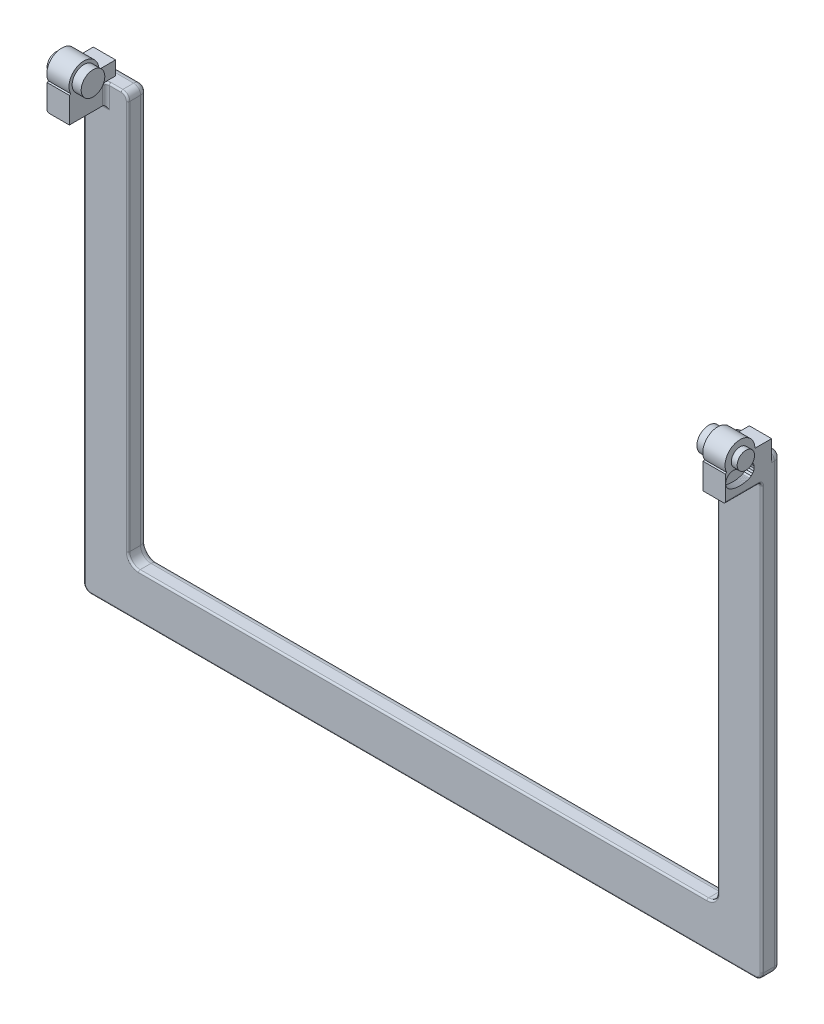
SolidWorks part; units mm, degrees
ref_plane "Спереди" through (0, 0, 0) normal (0, 0, 1) x (1, 0, 0)
ref_plane "Сверху" through (0, 0, 0) normal (0, 1, 0) x (1, 0, 0)
ref_plane "Справа" through (0, 0, 0) normal (1, 0, 0) x (0, 0, -1)
other "Configuration Table"
sketch "Foot_crossbar_profile" plane through (0, 0, 0) normal (0, 0, 1) x (1, 0, 0)
  line L0 (-0.6, -9) -> (190.6, -9)
  line L1 (192.6, -7) -> (192.6, 1.8)
  line L2 (190.6, 3.8) -> (-0.6, 3.8)
  line L3 (-2.6, 1.8) -> (-2.6, -7)
  arc A0 (190.6, -9) -> (192.6, -7) centre (190.6, -7) ccw
  arc A1 (192.6, 1.8) -> (190.6, 3.8) centre (190.6, 1.8) ccw
  arc A2 (-0.6, 3.8) -> (-2.6, 1.8) centre (-0.6, 1.8) ccw
  arc A3 (-2.6, -7) -> (-0.6, -9) centre (-0.6, -7) ccw
sketch "Right_leg_profile" plane through (0, 0, 0) normal (0, 0, 1) x (1, 0, 0)
  line L0 (181.8, -6.6) -> (190.6, -6.6)
  line L1 (192.6, -4.6) -> (192.6, 123)
  line L2 (190.6, 125) -> (181.8, 125)
  line L3 (179.8, 123) -> (179.8, -4.6)
  arc A0 (190.6, -6.6) -> (192.6, -4.6) centre (190.6, -4.6) ccw
  arc A1 (192.6, 123) -> (190.6, 125) centre (190.6, 123) ccw
  arc A2 (181.8, 125) -> (179.8, 123) centre (181.8, 123) ccw
  arc A3 (179.8, -4.6) -> (181.8, -6.6) centre (181.8, -4.6) ccw
sketch "Pivot_neck_0_profile" plane through (0, 0, 0) normal (1, 0, 0) x (0, 0, -1)
  line L0 (15.3, 115.4) -> (15.3, 125)
  line L1 (15.3, 125) -> (6.2, 125)
  line L2 (6.2, 125) -> (2, 122.8)
  line L3 (2, 122.8) -> (2, 115.4)
  line L4 (2, 115.4) -> (15.3, 115.4)
sketch "Pivot_lug_0_profile" plane through (0, 0, 0) normal (1, 0, 0) x (0, 0, -1)
  circle A0 centre (6.2, 125) radius 4.3
sketch "Captive_axle_0_profile" plane through (0, 0, 0) normal (1, 0, 0) x (0, 0, -1)
  circle A0 centre (6.2, 125) radius 2.5
sketch "Blind_rotation_groove_0_profile" plane through (0, 0, 0) normal (1, 0, 0) x (0, 0, -1)
  line L0 (8.9553, 118.3481) -> (8.7362, 118.2615)
  line L1 (8.7362, 118.2615) -> (8.5144, 118.1821)
  line L2 (8.5144, 118.1821) -> (8.29, 118.11)
  line L3 (8.29, 118.11) -> (8.0635, 118.0453)
  line L4 (8.0635, 118.0453) -> (7.8349, 117.9881)
  line L5 (7.8349, 117.9881) -> (7.6047, 117.9383)
  line L6 (7.6047, 117.9383) -> (7.3728, 117.8962)
  line L7 (7.3728, 117.8962) -> (7.1398, 117.8616)
  line L8 (7.1398, 117.8616) -> (6.9057, 117.8347)
  line L9 (6.9057, 117.8347) -> (6.6709, 117.8154)
  line L10 (6.6709, 117.8154) -> (6.4356, 117.8039)
  line L11 (6.4356, 117.8039) -> (6.2, 117.8)
  line L12 (6.2, 117.8) -> (5.9644, 117.8039)
  line L13 (5.9644, 117.8039) -> (5.7291, 117.8154)
  line L14 (5.7291, 117.8154) -> (5.4943, 117.8347)
  line L15 (5.4943, 117.8347) -> (5.2602, 117.8616)
  line L16 (5.2602, 117.8616) -> (5.0272, 117.8962)
  line L17 (5.0272, 117.8962) -> (4.7953, 117.9383)
  line L18 (4.7953, 117.9383) -> (4.5651, 117.9881)
  line L19 (4.5651, 117.9881) -> (4.3365, 118.0453)
  line L20 (4.3365, 118.0453) -> (4.11, 118.11)
  line L21 (4.11, 118.11) -> (3.8856, 118.1821)
  line L22 (3.8856, 118.1821) -> (3.6638, 118.2615)
  line L23 (3.6638, 118.2615) -> (3.4447, 118.3481)
  line L24 (3.4447, 118.3481) -> (2.9473, 118.6352)
  line L25 (2.9473, 118.6352) -> (2.5412, 119.0413)
  line L26 (2.5412, 119.0413) -> (2.254, 119.5387)
  line L27 (2.254, 119.5387) -> (2.1054, 120.0934)
  line L28 (2.1054, 120.0934) -> (2.1054, 120.6678)
  line L29 (2.1054, 120.6678) -> (2.254, 121.2225)
  line L30 (2.254, 121.2225) -> (2.5412, 121.7199)
  line L31 (2.5412, 121.7199) -> (2.9473, 122.126)
  line L32 (2.9473, 122.126) -> (3.4447, 122.4131)
  line L33 (3.4447, 122.4131) -> (3.9994, 122.5618)
  line L34 (3.9994, 122.5618) -> (4.5737, 122.5618)
  line L35 (4.5737, 122.5618) -> (5.1285, 122.4131)
  line L36 (5.1285, 122.4131) -> (5.2137, 122.3795)
  line L37 (5.2137, 122.3795) -> (5.3, 122.3486)
  line L38 (5.3, 122.3486) -> (5.3872, 122.3206)
  line L39 (5.3872, 122.3206) -> (5.4753, 122.2954)
  line L40 (5.4753, 122.2954) -> (5.5642, 122.2731)
  line L41 (5.5642, 122.2731) -> (5.6537, 122.2538)
  line L42 (5.6537, 122.2538) -> (5.7439, 122.2374)
  line L43 (5.7439, 122.2374) -> (5.8345, 122.224)
  line L44 (5.8345, 122.224) -> (5.9256, 122.2135)
  line L45 (5.9256, 122.2135) -> (6.0169, 122.206)
  line L46 (6.0169, 122.206) -> (6.1084, 122.2015)
  line L47 (6.1084, 122.2015) -> (6.2, 122.2)
  line L48 (6.2, 122.2) -> (6.2916, 122.2015)
  line L49 (6.2916, 122.2015) -> (6.3831, 122.206)
  line L50 (6.3831, 122.206) -> (6.4744, 122.2135)
  line L51 (6.4744, 122.2135) -> (6.5655, 122.224)
  line L52 (6.5655, 122.224) -> (6.6561, 122.2374)
  line L53 (6.6561, 122.2374) -> (6.7463, 122.2538)
  line L54 (6.7463, 122.2538) -> (6.8358, 122.2731)
  line L55 (6.8358, 122.2731) -> (6.9247, 122.2954)
  line L56 (6.9247, 122.2954) -> (7.0128, 122.3206)
  line L57 (7.0128, 122.3206) -> (7.1, 122.3486)
  line L58 (7.1, 122.3486) -> (7.1863, 122.3795)
  line L59 (7.1863, 122.3795) -> (7.2715, 122.4131)
  line L60 (7.2715, 122.4131) -> (7.8263, 122.5618)
  line L61 (7.8263, 122.5618) -> (8.4006, 122.5618)
  line L62 (8.4006, 122.5618) -> (8.9553, 122.4131)
  line L63 (8.9553, 122.4131) -> (9.4527, 122.126)
  line L64 (9.4527, 122.126) -> (9.8588, 121.7199)
  line L65 (9.8588, 121.7199) -> (10.146, 121.2225)
  line L66 (10.146, 121.2225) -> (10.2946, 120.6678)
  line L67 (10.2946, 120.6678) -> (10.2946, 120.0934)
  line L68 (10.2946, 120.0934) -> (10.146, 119.5387)
  line L69 (10.146, 119.5387) -> (9.8588, 119.0413)
  line L70 (9.8588, 119.0413) -> (9.4527, 118.6352)
  line L71 (9.4527, 118.6352) -> (8.9553, 118.3481)
sketch "Pivot_neck_1_profile" plane through (0, 0, 0) normal (1, 0, 0) x (0, 0, -1)
  line L0 (15.3, 115.4) -> (15.3, 125)
  line L1 (15.3, 125) -> (6.2, 125)
  line L2 (6.2, 125) -> (2, 122.8)
  line L3 (2, 122.8) -> (2, 115.4)
  line L4 (2, 115.4) -> (15.3, 115.4)
sketch "Pivot_lug_1_profile" plane through (0, 0, 0) normal (1, 0, 0) x (0, 0, -1)
  circle A0 centre (6.2, 125) radius 4.3
sketch "Captive_axle_1_profile" plane through (0, 0, 0) normal (1, 0, 0) x (0, 0, -1)
  circle A0 centre (6.2, 125) radius 2.5
sketch "Blind_rotation_groove_1_profile" plane through (0, 0, 0) normal (1, 0, 0) x (0, 0, -1)
  line L0 (8.9553, 118.3481) -> (8.7362, 118.2615)
  line L1 (8.7362, 118.2615) -> (8.5144, 118.1821)
  line L2 (8.5144, 118.1821) -> (8.29, 118.11)
  line L3 (8.29, 118.11) -> (8.0635, 118.0453)
  line L4 (8.0635, 118.0453) -> (7.8349, 117.9881)
  line L5 (7.8349, 117.9881) -> (7.6047, 117.9383)
  line L6 (7.6047, 117.9383) -> (7.3728, 117.8962)
  line L7 (7.3728, 117.8962) -> (7.1398, 117.8616)
  line L8 (7.1398, 117.8616) -> (6.9057, 117.8347)
  line L9 (6.9057, 117.8347) -> (6.6709, 117.8154)
  line L10 (6.6709, 117.8154) -> (6.4356, 117.8039)
  line L11 (6.4356, 117.8039) -> (6.2, 117.8)
  line L12 (6.2, 117.8) -> (5.9644, 117.8039)
  line L13 (5.9644, 117.8039) -> (5.7291, 117.8154)
  line L14 (5.7291, 117.8154) -> (5.4943, 117.8347)
  line L15 (5.4943, 117.8347) -> (5.2602, 117.8616)
  line L16 (5.2602, 117.8616) -> (5.0272, 117.8962)
  line L17 (5.0272, 117.8962) -> (4.7953, 117.9383)
  line L18 (4.7953, 117.9383) -> (4.5651, 117.9881)
  line L19 (4.5651, 117.9881) -> (4.3365, 118.0453)
  line L20 (4.3365, 118.0453) -> (4.11, 118.11)
  line L21 (4.11, 118.11) -> (3.8856, 118.1821)
  line L22 (3.8856, 118.1821) -> (3.6638, 118.2615)
  line L23 (3.6638, 118.2615) -> (3.4447, 118.3481)
  line L24 (3.4447, 118.3481) -> (2.9473, 118.6352)
  line L25 (2.9473, 118.6352) -> (2.5412, 119.0413)
  line L26 (2.5412, 119.0413) -> (2.254, 119.5387)
  line L27 (2.254, 119.5387) -> (2.1054, 120.0934)
  line L28 (2.1054, 120.0934) -> (2.1054, 120.6678)
  line L29 (2.1054, 120.6678) -> (2.254, 121.2225)
  line L30 (2.254, 121.2225) -> (2.5412, 121.7199)
  line L31 (2.5412, 121.7199) -> (2.9473, 122.126)
  line L32 (2.9473, 122.126) -> (3.4447, 122.4131)
  line L33 (3.4447, 122.4131) -> (3.9994, 122.5618)
  line L34 (3.9994, 122.5618) -> (4.5737, 122.5618)
  line L35 (4.5737, 122.5618) -> (5.1285, 122.4131)
  line L36 (5.1285, 122.4131) -> (5.2137, 122.3795)
  line L37 (5.2137, 122.3795) -> (5.3, 122.3486)
  line L38 (5.3, 122.3486) -> (5.3872, 122.3206)
  line L39 (5.3872, 122.3206) -> (5.4753, 122.2954)
  line L40 (5.4753, 122.2954) -> (5.5642, 122.2731)
  line L41 (5.5642, 122.2731) -> (5.6537, 122.2538)
  line L42 (5.6537, 122.2538) -> (5.7439, 122.2374)
  line L43 (5.7439, 122.2374) -> (5.8345, 122.224)
  line L44 (5.8345, 122.224) -> (5.9256, 122.2135)
  line L45 (5.9256, 122.2135) -> (6.0169, 122.206)
  line L46 (6.0169, 122.206) -> (6.1084, 122.2015)
  line L47 (6.1084, 122.2015) -> (6.2, 122.2)
  line L48 (6.2, 122.2) -> (6.2916, 122.2015)
  line L49 (6.2916, 122.2015) -> (6.3831, 122.206)
  line L50 (6.3831, 122.206) -> (6.4744, 122.2135)
  line L51 (6.4744, 122.2135) -> (6.5655, 122.224)
  line L52 (6.5655, 122.224) -> (6.6561, 122.2374)
  line L53 (6.6561, 122.2374) -> (6.7463, 122.2538)
  line L54 (6.7463, 122.2538) -> (6.8358, 122.2731)
  line L55 (6.8358, 122.2731) -> (6.9247, 122.2954)
  line L56 (6.9247, 122.2954) -> (7.0128, 122.3206)
  line L57 (7.0128, 122.3206) -> (7.1, 122.3486)
  line L58 (7.1, 122.3486) -> (7.1863, 122.3795)
  line L59 (7.1863, 122.3795) -> (7.2715, 122.4131)
  line L60 (7.2715, 122.4131) -> (7.8263, 122.5618)
  line L61 (7.8263, 122.5618) -> (8.4006, 122.5618)
  line L62 (8.4006, 122.5618) -> (8.9553, 122.4131)
  line L63 (8.9553, 122.4131) -> (9.4527, 122.126)
  line L64 (9.4527, 122.126) -> (9.8588, 121.7199)
  line L65 (9.8588, 121.7199) -> (10.146, 121.2225)
  line L66 (10.146, 121.2225) -> (10.2946, 120.6678)
  line L67 (10.2946, 120.6678) -> (10.2946, 120.0934)
  line L68 (10.2946, 120.0934) -> (10.146, 119.5387)
  line L69 (10.146, 119.5387) -> (9.8588, 119.0413)
  line L70 (9.8588, 119.0413) -> (9.4527, 118.6352)
  line L71 (9.4527, 118.6352) -> (8.9553, 118.3481)
sketch "Left_leg_profile" plane through (0, 0, 0) normal (0, 0, 1) x (1, 0, 0)
  line L0 (-0.6, -6.6) -> (8.2, -6.6)
  line L1 (10.2, -4.6) -> (10.2, 119)
  line L2 (8.2, 121) -> (-0.6, 121)
  line L3 (-2.6, 119) -> (-2.6, -4.6)
  arc A0 (8.2, -6.6) -> (10.2, -4.6) centre (8.2, -4.6) ccw
  arc A1 (10.2, 119) -> (8.2, 121) centre (8.2, 119) ccw
  arc A2 (-0.6, 121) -> (-2.6, 119) centre (-0.6, 119) ccw
  arc A3 (-2.6, -4.6) -> (-0.6, -6.6) centre (-0.6, -4.6) ccw
extrude "Left_leg" add sketch "Left_leg_profile" along normal blind 5.6 from offset 18.1
sketch "Эскиз2" plane through (0, 0, 0) normal (0, 0, 1) x (1, 0, 0)
  line L0 (-0.6, -9) -> (190.6, -9)
  line L1 (192.6, -7) -> (192.6, 1.8)
  line L2 (190.6, 3.8) -> (-0.6, 3.8)
  line L3 (-2.6, 1.8) -> (-2.6, -7)
  arc A0 (190.6, -9) -> (192.6, -7) centre (190.6, -7) ccw
  arc A1 (192.6, 1.8) -> (190.6, 3.8) centre (190.6, 1.8) ccw
  arc A2 (-0.6, 3.8) -> (-2.6, 1.8) centre (-0.6, 1.8) ccw
  arc A3 (-2.6, -7) -> (-0.6, -9) centre (-0.6, -7) ccw
extrude "Foot_crossbar" add sketch "Эскиз2" along normal blind 5.6 from offset 18.1
sketch "Эскиз3" plane through (0, 0, 0) normal (0, 0, 1) x (1, 0, 0)
  line L0 (181.8, -6.6) -> (190.6, -6.6)
  line L1 (192.6, -4.6) -> (192.6, 119)
  line L2 (190.6, 121) -> (181.8, 121)
  line L3 (179.8, 119) -> (179.8, -4.6)
  arc A0 (190.6, -6.6) -> (192.6, -4.6) centre (190.6, -4.6) ccw
  arc A1 (192.6, 119) -> (190.6, 121) centre (190.6, 119) ccw
  arc A2 (181.8, 121) -> (179.8, 119) centre (181.8, 119) ccw
  arc A3 (179.8, -4.6) -> (181.8, -6.6) centre (181.8, -4.6) ccw
extrude "Right_leg" add sketch "Эскиз3" along normal blind 5.6 from offset 18.1
sketch "Эскиз4" plane through (0, 0, 0) normal (1, 0, 0) x (0, 0, -1)
  line L0 (15.3, 115.4) -> (15.3, 125)
  line L1 (15.3, 125) -> (6.2, 125)
  line L2 (6.2, 125) -> (2, 122.8)
  line L3 (2, 122.8) -> (2, 115.4)
  line L4 (2, 115.4) -> (15.3, 115.4)
extrude "Pivot_neck_0" add sketch "Эскиз4" along normal blind 6.4 from offset 2.6
sketch "Эскиз5" plane through (0, 0, 0) normal (1, 0, 0) x (0, 0, -1)
  circle A0 centre (6.2, 125) radius 4.3
extrude "Pivot_lug_0" add sketch "Эскиз5" along normal blind 6.4 from offset 2.6
sketch "Glass_keeper_0_profile" plane through (0, 0, 0) normal (1, 0, 0) x (0, 0, -1)
  circle A0 centre (6.2, 125) radius 3.4
extrude "Glass_keeper_0" add sketch "Glass_keeper_0_profile" along normal blind 2.8 from offset 3.6
sketch "Эскиз7" plane through (0, 0, 0) normal (1, 0, 0) x (0, 0, -1)
  circle A0 centre (6.2, 125) radius 2.5
extrude "Captive_axle_0" add sketch "Эскиз7" along normal blind 2 from offset 4.3
sketch "Эскиз8" plane through (0, 0, 0) normal (1, 0, 0) x (0, 0, -1)
  line L0 (8.9553, 118.3481) -> (8.7362, 118.2615)
  line L1 (8.7362, 118.2615) -> (8.5144, 118.1821)
  line L2 (8.5144, 118.1821) -> (8.29, 118.11)
  line L3 (8.29, 118.11) -> (8.0635, 118.0453)
  line L4 (8.0635, 118.0453) -> (7.8349, 117.9881)
  line L5 (7.8349, 117.9881) -> (7.6047, 117.9383)
  line L6 (7.6047, 117.9383) -> (7.3728, 117.8962)
  line L7 (7.3728, 117.8962) -> (7.1398, 117.8616)
  line L8 (7.1398, 117.8616) -> (6.9057, 117.8347)
  line L9 (6.9057, 117.8347) -> (6.6709, 117.8154)
  line L10 (6.6709, 117.8154) -> (6.4356, 117.8039)
  line L11 (6.4356, 117.8039) -> (6.2, 117.8)
  line L12 (6.2, 117.8) -> (5.9644, 117.8039)
  line L13 (5.9644, 117.8039) -> (5.7291, 117.8154)
  line L14 (5.7291, 117.8154) -> (5.4943, 117.8347)
  line L15 (5.4943, 117.8347) -> (5.2602, 117.8616)
  line L16 (5.2602, 117.8616) -> (5.0272, 117.8962)
  line L17 (5.0272, 117.8962) -> (4.7953, 117.9383)
  line L18 (4.7953, 117.9383) -> (4.5651, 117.9881)
  line L19 (4.5651, 117.9881) -> (4.3365, 118.0453)
  line L20 (4.3365, 118.0453) -> (4.11, 118.11)
  line L21 (4.11, 118.11) -> (3.8856, 118.1821)
  line L22 (3.8856, 118.1821) -> (3.6638, 118.2615)
  line L23 (3.6638, 118.2615) -> (3.4447, 118.3481)
  line L24 (3.4447, 118.3481) -> (2.9473, 118.6352)
  line L25 (2.9473, 118.6352) -> (2.5412, 119.0413)
  line L26 (2.5412, 119.0413) -> (2.254, 119.5387)
  line L27 (2.254, 119.5387) -> (2.1054, 120.0934)
  line L28 (2.1054, 120.0934) -> (2.1054, 120.6678)
  line L29 (2.1054, 120.6678) -> (2.254, 121.2225)
  line L30 (2.254, 121.2225) -> (2.5412, 121.7199)
  line L31 (2.5412, 121.7199) -> (2.9473, 122.126)
  line L32 (2.9473, 122.126) -> (3.4447, 122.4131)
  line L33 (3.4447, 122.4131) -> (3.9994, 122.5618)
  line L34 (3.9994, 122.5618) -> (4.5737, 122.5618)
  line L35 (4.5737, 122.5618) -> (5.1285, 122.4131)
  line L36 (5.1285, 122.4131) -> (5.2137, 122.3795)
  line L37 (5.2137, 122.3795) -> (5.3, 122.3486)
  line L38 (5.3, 122.3486) -> (5.3872, 122.3206)
  line L39 (5.3872, 122.3206) -> (5.4753, 122.2954)
  line L40 (5.4753, 122.2954) -> (5.5642, 122.2731)
  line L41 (5.5642, 122.2731) -> (5.6537, 122.2538)
  line L42 (5.6537, 122.2538) -> (5.7439, 122.2374)
  line L43 (5.7439, 122.2374) -> (5.8345, 122.224)
  line L44 (5.8345, 122.224) -> (5.9256, 122.2135)
  line L45 (5.9256, 122.2135) -> (6.0169, 122.206)
  line L46 (6.0169, 122.206) -> (6.1084, 122.2015)
  line L47 (6.1084, 122.2015) -> (6.2, 122.2)
  line L48 (6.2, 122.2) -> (6.2916, 122.2015)
  line L49 (6.2916, 122.2015) -> (6.3831, 122.206)
  line L50 (6.3831, 122.206) -> (6.4744, 122.2135)
  line L51 (6.4744, 122.2135) -> (6.5655, 122.224)
  line L52 (6.5655, 122.224) -> (6.6561, 122.2374)
  line L53 (6.6561, 122.2374) -> (6.7463, 122.2538)
  line L54 (6.7463, 122.2538) -> (6.8358, 122.2731)
  line L55 (6.8358, 122.2731) -> (6.9247, 122.2954)
  line L56 (6.9247, 122.2954) -> (7.0128, 122.3206)
  line L57 (7.0128, 122.3206) -> (7.1, 122.3486)
  line L58 (7.1, 122.3486) -> (7.1863, 122.3795)
  line L59 (7.1863, 122.3795) -> (7.2715, 122.4131)
  line L60 (7.2715, 122.4131) -> (7.8263, 122.5618)
  line L61 (7.8263, 122.5618) -> (8.4006, 122.5618)
  line L62 (8.4006, 122.5618) -> (8.9553, 122.4131)
  line L63 (8.9553, 122.4131) -> (9.4527, 122.126)
  line L64 (9.4527, 122.126) -> (9.8588, 121.7199)
  line L65 (9.8588, 121.7199) -> (10.146, 121.2225)
  line L66 (10.146, 121.2225) -> (10.2946, 120.6678)
  line L67 (10.2946, 120.6678) -> (10.2946, 120.0934)
  line L68 (10.2946, 120.0934) -> (10.146, 119.5387)
  line L69 (10.146, 119.5387) -> (9.8588, 119.0413)
  line L70 (9.8588, 119.0413) -> (9.4527, 118.6352)
  line L71 (9.4527, 118.6352) -> (8.9553, 118.3481)
extrude "Blind_rotation_groove_0" cut sketch "Эскиз8" along normal blind 2.1 from offset 2.7
sketch "Эскиз9" plane through (0, 0, 0) normal (1, 0, 0) x (0, 0, -1)
  line L0 (15.3, 115.4) -> (15.3, 125)
  line L1 (15.3, 125) -> (6.2, 125)
  line L2 (6.2, 125) -> (2, 122.8)
  line L3 (2, 122.8) -> (2, 115.4)
  line L4 (2, 115.4) -> (15.3, 115.4)
extrude "Pivot_neck_1" add sketch "Эскиз9" along normal blind 6.4 from offset 186.2
sketch "Эскиз10" plane through (0, 0, 0) normal (1, 0, 0) x (0, 0, -1)
  circle A0 centre (6.2, 125) radius 4.3
extrude "Pivot_lug_1" add sketch "Эскиз10" along normal blind 6.4 from offset 186.2
sketch "Glass_keeper_1_profile" plane through (0, 0, 0) normal (1, 0, 0) x (0, 0, -1)
  circle A0 centre (6.2, 125) radius 3.4
extrude "Glass_keeper_1" add sketch "Glass_keeper_1_profile" along normal blind 2.8 from offset 183.6
sketch "Эскиз12" plane through (0, 0, 0) normal (1, 0, 0) x (0, 0, -1)
  circle A0 centre (6.2, 125) radius 2.5
extrude "Captive_axle_1" add sketch "Эскиз12" along normal blind 2 from offset 192.3
sketch "Эскиз13" plane through (0, 0, 0) normal (1, 0, 0) x (0, 0, -1)
  line L0 (8.9553, 118.3481) -> (8.7362, 118.2615)
  line L1 (8.7362, 118.2615) -> (8.5144, 118.1821)
  line L2 (8.5144, 118.1821) -> (8.29, 118.11)
  line L3 (8.29, 118.11) -> (8.0635, 118.0453)
  line L4 (8.0635, 118.0453) -> (7.8349, 117.9881)
  line L5 (7.8349, 117.9881) -> (7.6047, 117.9383)
  line L6 (7.6047, 117.9383) -> (7.3728, 117.8962)
  line L7 (7.3728, 117.8962) -> (7.1398, 117.8616)
  line L8 (7.1398, 117.8616) -> (6.9057, 117.8347)
  line L9 (6.9057, 117.8347) -> (6.6709, 117.8154)
  line L10 (6.6709, 117.8154) -> (6.4356, 117.8039)
  line L11 (6.4356, 117.8039) -> (6.2, 117.8)
  line L12 (6.2, 117.8) -> (5.9644, 117.8039)
  line L13 (5.9644, 117.8039) -> (5.7291, 117.8154)
  line L14 (5.7291, 117.8154) -> (5.4943, 117.8347)
  line L15 (5.4943, 117.8347) -> (5.2602, 117.8616)
  line L16 (5.2602, 117.8616) -> (5.0272, 117.8962)
  line L17 (5.0272, 117.8962) -> (4.7953, 117.9383)
  line L18 (4.7953, 117.9383) -> (4.5651, 117.9881)
  line L19 (4.5651, 117.9881) -> (4.3365, 118.0453)
  line L20 (4.3365, 118.0453) -> (4.11, 118.11)
  line L21 (4.11, 118.11) -> (3.8856, 118.1821)
  line L22 (3.8856, 118.1821) -> (3.6638, 118.2615)
  line L23 (3.6638, 118.2615) -> (3.4447, 118.3481)
  line L24 (3.4447, 118.3481) -> (2.9473, 118.6352)
  line L25 (2.9473, 118.6352) -> (2.5412, 119.0413)
  line L26 (2.5412, 119.0413) -> (2.254, 119.5387)
  line L27 (2.254, 119.5387) -> (2.1054, 120.0934)
  line L28 (2.1054, 120.0934) -> (2.1054, 120.6678)
  line L29 (2.1054, 120.6678) -> (2.254, 121.2225)
  line L30 (2.254, 121.2225) -> (2.5412, 121.7199)
  line L31 (2.5412, 121.7199) -> (2.9473, 122.126)
  line L32 (2.9473, 122.126) -> (3.4447, 122.4131)
  line L33 (3.4447, 122.4131) -> (3.9994, 122.5618)
  line L34 (3.9994, 122.5618) -> (4.5737, 122.5618)
  line L35 (4.5737, 122.5618) -> (5.1285, 122.4131)
  line L36 (5.1285, 122.4131) -> (5.2137, 122.3795)
  line L37 (5.2137, 122.3795) -> (5.3, 122.3486)
  line L38 (5.3, 122.3486) -> (5.3872, 122.3206)
  line L39 (5.3872, 122.3206) -> (5.4753, 122.2954)
  line L40 (5.4753, 122.2954) -> (5.5642, 122.2731)
  line L41 (5.5642, 122.2731) -> (5.6537, 122.2538)
  line L42 (5.6537, 122.2538) -> (5.7439, 122.2374)
  line L43 (5.7439, 122.2374) -> (5.8345, 122.224)
  line L44 (5.8345, 122.224) -> (5.9256, 122.2135)
  line L45 (5.9256, 122.2135) -> (6.0169, 122.206)
  line L46 (6.0169, 122.206) -> (6.1084, 122.2015)
  line L47 (6.1084, 122.2015) -> (6.2, 122.2)
  line L48 (6.2, 122.2) -> (6.2916, 122.2015)
  line L49 (6.2916, 122.2015) -> (6.3831, 122.206)
  line L50 (6.3831, 122.206) -> (6.4744, 122.2135)
  line L51 (6.4744, 122.2135) -> (6.5655, 122.224)
  line L52 (6.5655, 122.224) -> (6.6561, 122.2374)
  line L53 (6.6561, 122.2374) -> (6.7463, 122.2538)
  line L54 (6.7463, 122.2538) -> (6.8358, 122.2731)
  line L55 (6.8358, 122.2731) -> (6.9247, 122.2954)
  line L56 (6.9247, 122.2954) -> (7.0128, 122.3206)
  line L57 (7.0128, 122.3206) -> (7.1, 122.3486)
  line L58 (7.1, 122.3486) -> (7.1863, 122.3795)
  line L59 (7.1863, 122.3795) -> (7.2715, 122.4131)
  line L60 (7.2715, 122.4131) -> (7.8263, 122.5618)
  line L61 (7.8263, 122.5618) -> (8.4006, 122.5618)
  line L62 (8.4006, 122.5618) -> (8.9553, 122.4131)
  line L63 (8.9553, 122.4131) -> (9.4527, 122.126)
  line L64 (9.4527, 122.126) -> (9.8588, 121.7199)
  line L65 (9.8588, 121.7199) -> (10.146, 121.2225)
  line L66 (10.146, 121.2225) -> (10.2946, 120.6678)
  line L67 (10.2946, 120.6678) -> (10.2946, 120.0934)
  line L68 (10.2946, 120.0934) -> (10.146, 119.5387)
  line L69 (10.146, 119.5387) -> (9.8588, 119.0413)
  line L70 (9.8588, 119.0413) -> (9.4527, 118.6352)
  line L71 (9.4527, 118.6352) -> (8.9553, 118.3481)
extrude "Blind_rotation_groove_1" cut sketch "Эскиз13" along normal blind 2.1 from offset 190.6
fillet "Stand_leg_root_round" radius 3 2 edges at (10.2, 3.8, -15.3) (179.8, 3.8, -15.3)
fillet "Pivot_neck_root_round" radius 1 4 edges at (0.6, 115.4, -12.5) (3.8, 118.2, -12.5) (189.4, 115.4, -12.5) (186.2, 118.2, -12.5)
fillet "Stand_contact_round" radius 2 16 edges at (-2.6, 56, -18.1) (-2.0142, -8.4142, -18.1) (95, -9, -18.1) (3.8, 121, -18.1) (192.0142, -8.4142, -18.1) (9.6142, 120.4142, -18.1) (192.6, 56, -18.1) (10.2, 62.9, -18.1) (192.0142, 120.4142, -18.1) (11.0787, 4.6787, -18.1) (186.2, 121, -18.1) (95, 3.8, -18.1) (180.3858, 120.4142, -18.1) (178.9213, 4.6787, -18.1) (179.8, 62.9, -18.1) (-2.0142, 120.4142, -18.1)
fillet "Stand_front_edge_round" radius 0.5 20 edges at (185.9071, 121, -12.2071) (183.5, 121, -12.5) (180.3858, 120.4142, -12.5) (4.0929, 121, -12.2071) (6.5, 121, -12.5) (9.6142, 120.4142, -12.5) (-2.6, 115.4, -6.75) (-2.6, 115.1071, -12.2071) (192.6, 115.4, -6.75) (192.6, 115.1071, -12.2071) (10.2, 62.9, -12.5) (11.0787, 4.6787, -12.5) (95, -9, -12.5) (95, 3.8, -12.5) (192.0142, -8.4142, -12.5) (178.9213, 4.6787, -12.5) (192.6, 53.7, -12.5) (179.8, 62.9, -12.5) (-2.0142, -8.4142, -12.5) (-2.6, 53.7, -12.5)
